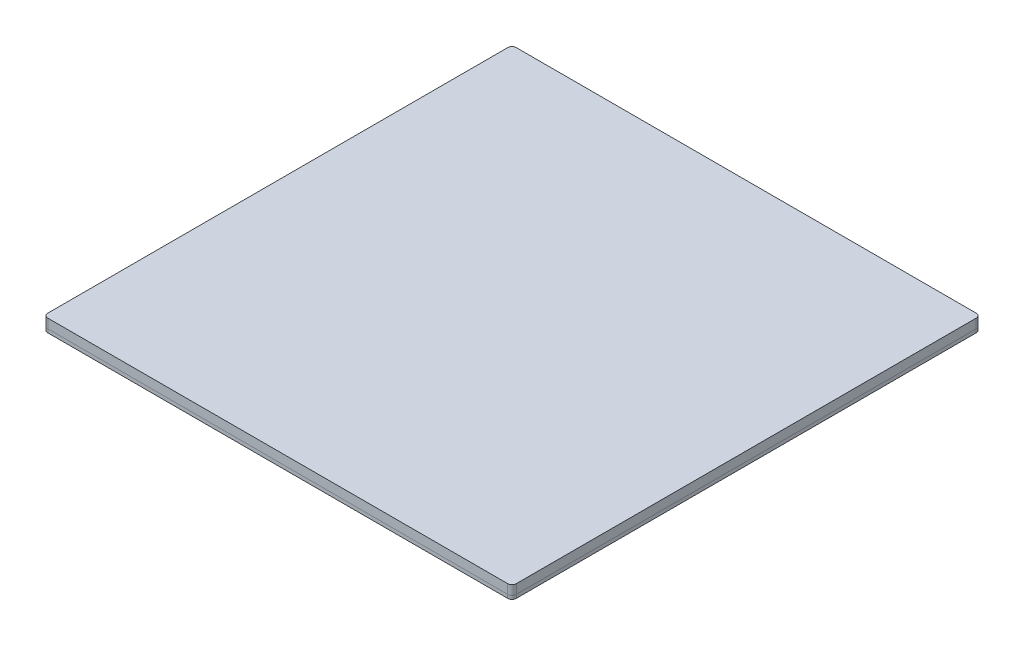
SolidWorks part; units mm, degrees
ref_plane "Front Plane" through (0, 0, 0) normal (0, 0, 1) x (1, 0, 0)
ref_plane "Top Plane" through (0, 0, 0) normal (0, 1, 0) x (1, 0, 0)
ref_plane "Right Plane" through (0, 0, 0) normal (1, 0, 0) x (0, 0, -1)
sketch "Sketch1" plane through (0, 0, 0) normal (0, 1, 0) x (1, 0, 0)
  line L1 (-110, -110) -> (110, -110)
  line L2 (-110, -110) -> (-110, 110)
  line L3 (-110, 110) -> (110, 110)
  line L4 (110, -110) -> (110, 110)
  line L5 (-110, -110) -> (110, 110) construction
  line L6 (-110, 110) -> (110, -110) construction
  point P0 (0, 0)
  dimension "D1" = 220
extrude "Boss-Extrude1" add sketch "Sketch1" along normal blind 4.35
sketch "Sketch2" plane through (0, 0, 0) normal (0, -1, 0) x (1, 0, 0)
  line L4 (110, -110) -> (110, 110)
  line L5 (110, 110) -> (-110, 110)
  line L6 (-110, 110) -> (-110, -110)
  line L7 (-110, -110) -> (110, -110)
  line L8 (110, -110) -> (110, 110)
  line L9 (110, 110) -> (-110, 110)
  line L10 (-110, 110) -> (-110, -110)
  line L11 (-110, -110) -> (110, -110)
  dimension "D1" = 0
extrude "Boss-Extrude2" add sketch "Sketch2" along normal blind 1.65 separate body
sketch "Sketch4" plane through (0, 0, 0) normal (0, 1, 0) x (1, 0, 0)
  line L0 (-104.5, 104.5) -> (104.5, 104.5) construction
  line L1 (104.5, 104.5) -> (104.5, -104.5) construction
  line L2 (104.5, -104.5) -> (-104.5, -104.5) construction
  line L3 (-104.5, -104.5) -> (-104.5, 104.5) construction
  line L4 (110, 110) -> (-110, 110) construction
  line L5 (-110, 110) -> (-110, -110) construction
  circle A0 centre (-104.5, 104.5) radius 1.5
  circle A1 centre (104.5, 104.5) radius 1.5
  circle A2 centre (104.5, -104.5) radius 1.5
  circle A3 centre (-104.5, -104.5) radius 1.5
  point P8 (0, 104.5)
  point P11 (0, 110)
  point P12 (-104.5, 0)
  point P15 (-110, 0)
  dimension "D1" = 209
  dimension "D3" = 3
  dimension "D2" = 209
extrude "Cut-Extrude1" cut sketch "Sketch4" against normal through all
fillet "Fillet1" radius 2 4 edges at (110, 2.175, 110) (110, 2.175, -110) (-110, 2.175, -110) (-110, 2.175, 110)
fillet "Fillet2" radius 2 4 edges at (-110, -0.825, -110) (-110, -0.825, 110) (110, -0.825, -110) (110, -0.825, 110)
